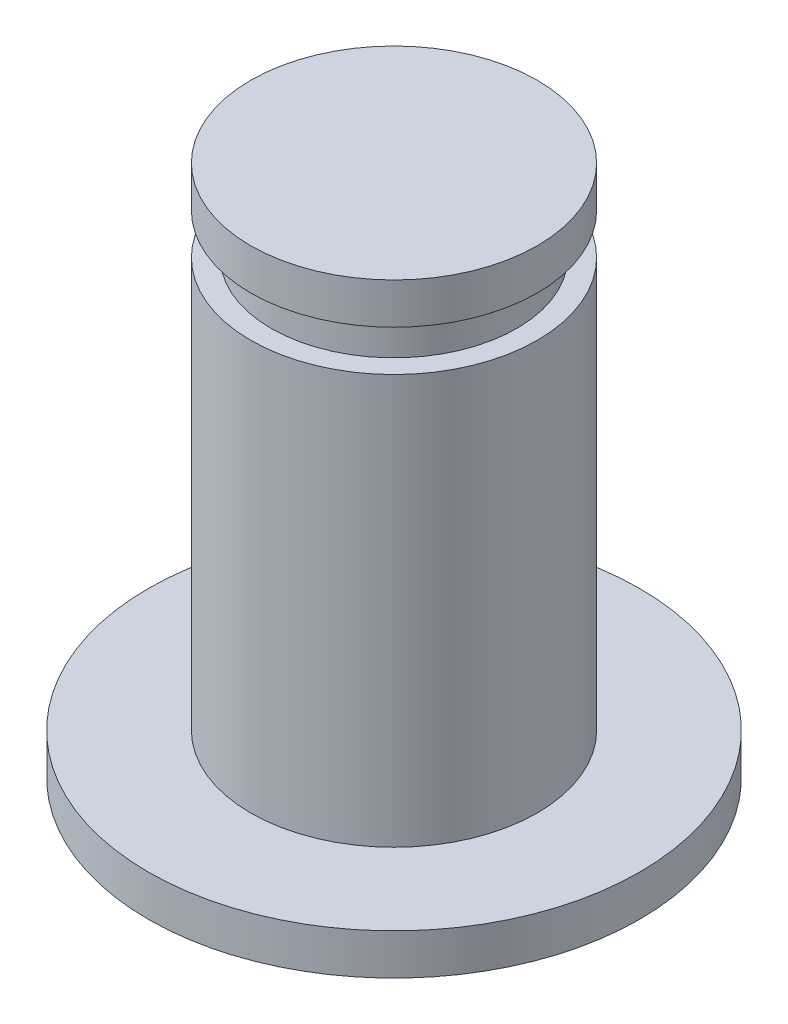
SolidWorks part; units mm, degrees
ref_plane "Front Plane" through (0, 0, 0) normal (0, 0, 1) x (1, 0, 0)
ref_plane "Top Plane" through (0, 0, 0) normal (0, 1, 0) x (1, 0, 0)
ref_plane "Right Plane" through (0, 0, 0) normal (1, 0, 0) x (0, 0, -1)
sketch "Esboço1" plane through (0, 0, 0) normal (0, 1, 0) x (1, 0, 0)
  circle A0 centre (0, 0) radius 6
  dimension "D1" = 12
extrude "Ressalto-extrusão1" add sketch "Esboço1" along normal blind 1
sketch "Esboço2" plane through (0, 1, 0) normal (0, 1, 0) x (1, 0, 0)
  circle A0 centre (0, 0) radius 3.5
  dimension "D1" = 7
extrude "Ressalto-extrusão2" add sketch "Esboço2" along normal blind 12
sketch "Esboço3" plane through (0, 13, 0) normal (0, 1, 0) x (1, 0, 0)
  circle A0 centre (0, 0) radius 3
  circle A1 centre (0, 0) radius 3.5
  circle A2 centre (0, 0) radius 3.5
  dimension "D2" = 0.5
  dimension "D1" = 0
extrude "Corte-extrusão1" cut sketch "Esboço3" against normal blind 1 from offset 1
